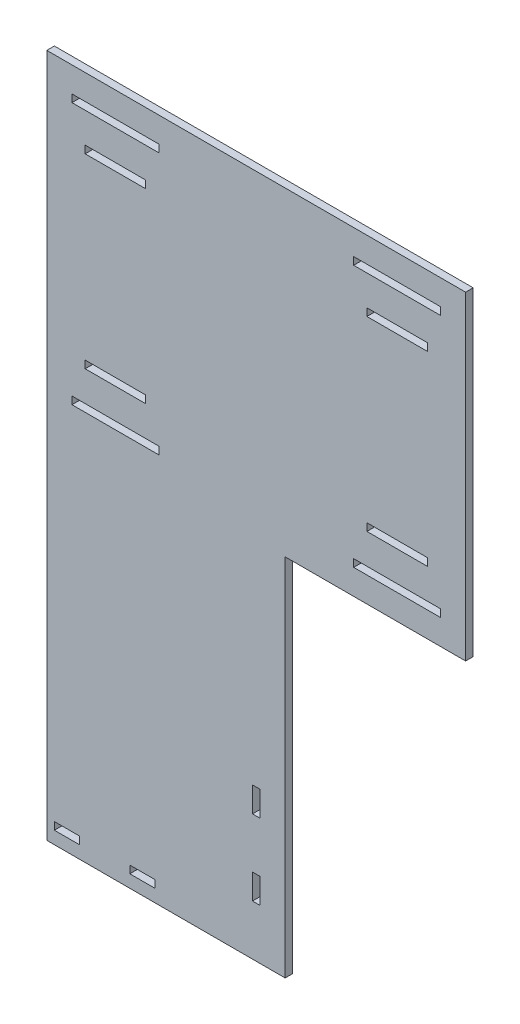
SolidWorks part; units mm, degrees
ref_plane "Front Plane" through (0, 0, 0) normal (0, 0, 1) x (1, 0, 0)
ref_plane "Top Plane" through (0, 0, 0) normal (0, 1, 0) x (1, 0, 0)
ref_plane "Right Plane" through (0, 0, 0) normal (1, 0, 0) x (0, 0, -1)
sketch "Sketch1" plane through (0, 0, 0) normal (0, 0, 1) x (1, 0, 0)
  line L0 (194.1449, 100) -> (-138.8551, 100)
  line L1 (-138.8551, 100) -> (-138.8551, -444)
  line L2 (-138.8551, -444) -> (194.1449, -444)
  line L3 (194.1449, -444) -> (194.1449, 100)
  line L89 (115.6449, 44) -> (115.6449, 50)
  line L90 (115.6449, 44) -> (163.6449, 44)
  line L91 (163.6449, 44) -> (163.6449, 50)
  line L92 (115.6449, 50) -> (163.6449, 50)
  line L93 (105.1449, 74) -> (105.1449, 80)
  line L94 (105.1449, 74) -> (174.1449, 74)
  line L95 (174.1449, 74) -> (174.1449, 80)
  line L96 (105.1449, 80) -> (174.1449, 80)
  line L97 (115.6449, -98) -> (115.6449, -104)
  line L98 (115.6449, -98) -> (163.6449, -98)
  line L99 (163.6449, -98) -> (163.6449, -104)
  line L100 (115.6449, -104) -> (163.6449, -104)
  line L101 (105.1449, -134) -> (105.1449, -128)
  line L102 (105.1449, -134) -> (174.1449, -134)
  line L103 (174.1449, -134) -> (174.1449, -128)
  line L104 (105.1449, -128) -> (174.1449, -128)
  line L152 (-118.8551, 74) -> (-118.8551, 80)
  line L153 (-118.8551, 80) -> (-49.8551, 80)
  line L154 (-49.8551, 74) -> (-49.8551, 80)
  line L155 (-118.8551, 74) -> (-49.8551, 74)
  line L156 (-108.3551, 44) -> (-108.3551, 50)
  line L157 (-108.3551, 50) -> (-60.3551, 50)
  line L158 (-60.3551, 44) -> (-60.3551, 50)
  line L159 (-108.3551, 44) -> (-60.3551, 44)
  line L160 (-108.3551, -98) -> (-108.3551, -104)
  line L161 (-108.3551, -104) -> (-60.3551, -104)
  line L162 (-60.3551, -98) -> (-60.3551, -104)
  line L163 (-108.3551, -98) -> (-60.3551, -98)
  line L164 (-118.8551, -134) -> (-118.8551, -128)
  line L165 (-118.8551, -128) -> (-49.8551, -128)
  line L166 (-49.8551, -134) -> (-49.8551, -128)
  line L167 (-118.8551, -134) -> (-49.8551, -134)
  line L173 (24.6449, -404) -> (30.6449, -404)
  line L174 (24.6449, -404) -> (24.6449, -384)
  line L175 (24.6449, -384) -> (30.6449, -384)
  line L176 (30.6449, -404) -> (30.6449, -384)
  line L177 (24.6449, -344) -> (30.6449, -344)
  line L178 (24.6449, -344) -> (24.6449, -324)
  line L179 (24.6449, -324) -> (30.6449, -324)
  line L180 (30.6449, -344) -> (30.6449, -324)
  line L184 (-52.8551, -434) -> (-52.8551, -428)
  line L185 (-52.8551, -434) -> (-72.8551, -434)
  line L186 (-72.8551, -434) -> (-72.8551, -428)
  line L187 (-52.8551, -428) -> (-72.8551, -428)
  line L188 (-112.8551, -434) -> (-112.8551, -428)
  line L189 (-112.8551, -434) -> (-132.8551, -434)
  line L190 (-132.8551, -434) -> (-132.8551, -428)
  line L191 (-112.8551, -428) -> (-132.8551, -428)
  point P0 (27.6449, -344)
  point P2 (27.6449, -404)
  point P22 (27.6449, -444)
  dimension "D2" = 20
  dimension "D3" = 69
  dimension "D4" = 2
  dimension "D5" = 24
  dimension "D6" = 20
  dimension "D7" = 24
  dimension "D8" = 20
  dimension "D9" = 48
  dimension "D10" = 6
  dimension "D11" = 208
  dimension "D12" = 10.5
  dimension "D13" = 40
  dimension "D14" = 10.5
  dimension "D15" = 310
  dimension "D16" = 6
  dimension "D17" = 142
  dimension "D18" = 6
  dimension "D19" = 224
  dimension "D22" = 6
  dimension "D23" = 20
  dimension "D24" = 40
  dimension "D26" = 6
  dimension "D27" = 20
  dimension "D28" = 40
  dimension "D30" = 6
  dimension "D31" = 10
extrude "Boss-Extrude1" add sketch "Sketch1" along normal blind 6
sketch "Sketch2" plane through (0, 0, 6) normal (0, 0, 1) x (1, 0, 0)
  line L1 (194.1449, -444) -> (50.6449, -444)
  line L2 (194.1449, -444) -> (194.1449, -154)
  line L3 (194.1449, -154) -> (50.6449, -154)
  line L4 (50.6449, -444) -> (50.6449, -154)
  line L5 (105.1449, -134) -> (174.1449, -134) construction
  line L6 (30.6449, -404) -> (30.6449, -384) construction
  dimension "D1" = 20
  dimension "D2" = 20
extrude "Cut-Extrude1" cut sketch "Sketch2" against normal blind 6
